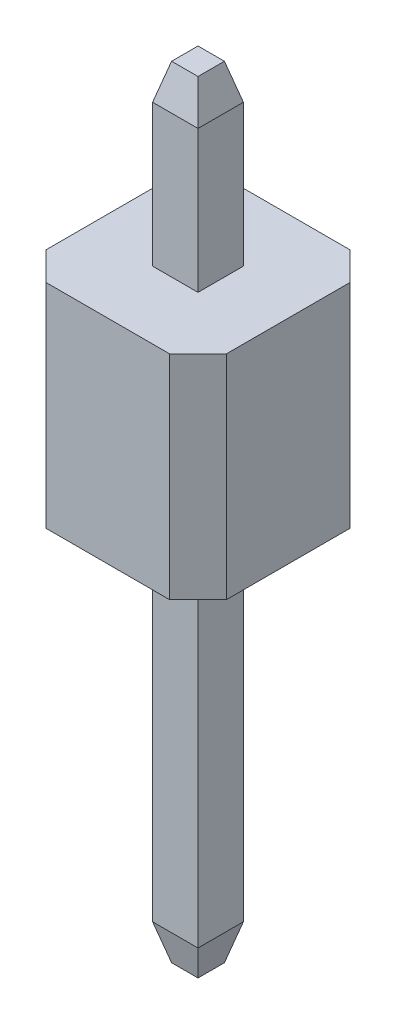
SolidWorks part; units mm, degrees
ref_plane "Front Plane" through (0, 0, 0) normal (0, 0, 1) x (1, 0, 0)
ref_plane "Top Plane" through (0, 0, 0) normal (0, 1, 0) x (1, 0, 0)
ref_plane "Right Plane" through (0, 0, 0) normal (1, 0, 0) x (0, 0, -1)
sketch "Sketch1" plane through (0, 0, 0) normal (0, 1, 0) x (1, 0, 0)
  line L1 (-1.27, -1.27) -> (1.27, -1.27)
  line L2 (-1.27, -1.27) -> (-1.27, 1.27)
  line L3 (-1.27, 1.27) -> (1.27, 1.27)
  line L4 (1.27, -1.27) -> (1.27, 1.27)
  line L5 (-1.27, -1.27) -> (1.27, 1.27) construction
  line L6 (-1.27, 1.27) -> (1.27, -1.27) construction
  point P0 (0, 0)
  dimension "D1" = 2.54
  dimension "D2" = 2.54
extrude "Boss-Extrude1" add sketch "Sketch1" along normal blind 3
chamfer "Chamfer1" distance 0.4 angle 45 4 edges at (-1.27, 1.5, -1.27) (1.27, 1.5, -1.27) (-1.27, 1.5, 1.27) (1.27, 1.5, 1.27)
sketch "Sketch2" plane through (0, 0, 0) normal (0, -1, 0) x (1, 0, 0)
  line L1 (-0.32, 0.32) -> (0.32, 0.32)
  line L2 (-0.32, 0.32) -> (-0.32, -0.32)
  line L3 (-0.32, -0.32) -> (0.32, -0.32)
  line L4 (0.32, 0.32) -> (0.32, -0.32)
  line L5 (-0.32, 0.32) -> (0.32, -0.32) construction
  line L6 (-0.32, -0.32) -> (0.32, 0.32) construction
  point P0 (0, 0)
  dimension "D1" = 0.64
extrude "Boss-Extrude2" add sketch "Sketch2" along normal blind 5 and the other way blind 5
sketch "Sketch3" plane through (0, 5, 0) normal (0, 1, 0) x (1, 0, 0)
  line L4 (0.32, -0.32) -> (0.32, 0.32)
  line L5 (0.32, 0.32) -> (-0.32, 0.32)
  line L6 (-0.32, 0.32) -> (-0.32, -0.32)
  line L7 (-0.32, -0.32) -> (0.32, -0.32)
  line L8 (0.32, -0.32) -> (0.32, 0.32)
  line L9 (0.32, 0.32) -> (-0.32, 0.32)
  line L10 (-0.32, 0.32) -> (-0.32, -0.32)
  line L11 (-0.32, -0.32) -> (0.32, -0.32)
  dimension "D1" = 0
extrude "Boss-Extrude3" add sketch "Sketch3" along normal blind 0.5 draft 15
mirror "Mirror1" about plane through (0, 0, 0) normal (0, 1, 0) of "Boss-Extrude3"
